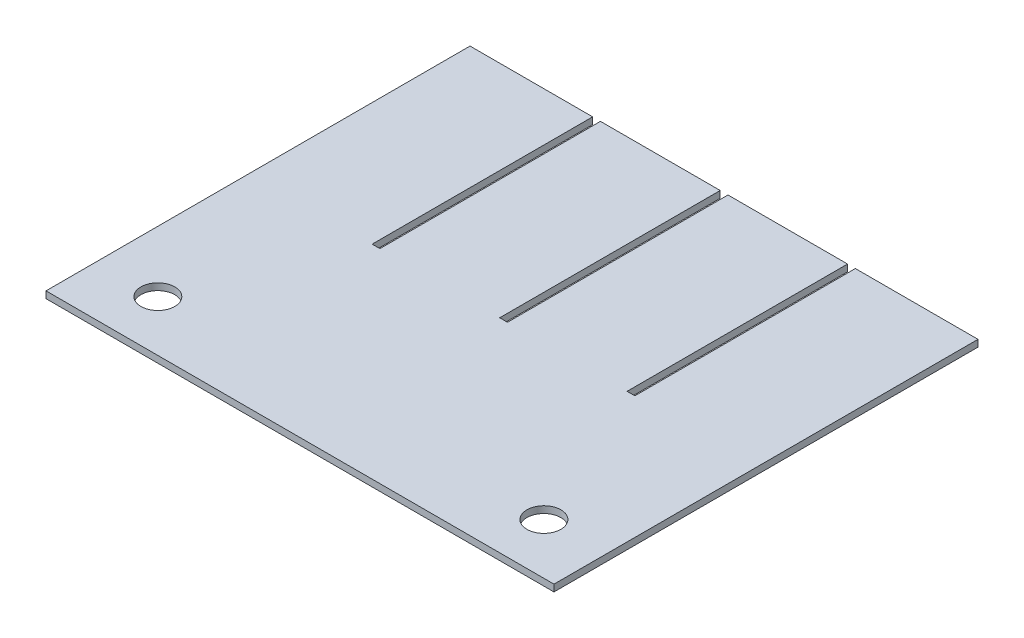
SolidWorks part; units mm, degrees
ref_plane "Front Plane" through (0, 0, 0) normal (0, 0, 1) x (1, 0, 0)
ref_plane "Top Plane" through (0, 0, 0) normal (0, 1, 0) x (1, 0, 0)
ref_plane "Right Plane" through (0, 0, 0) normal (1, 0, 0) x (0, 0, -1)
sketch "Sketch1" plane through (0, 0, 0) normal (0, 1, 0) x (1, 0, 0)
  line L0 (1.175, 62.5) -> (36.425, 62.5)
  line L1 (-74.875, 62.5) -> (-38.725, 62.5)
  line L2 (-74.875, 62.5) -> (-74.875, -62.5)
  line L3 (-74.875, -62.5) -> (74.875, -62.5)
  line L4 (74.875, 62.5) -> (74.875, -62.5)
  line L5 (-74.875, 62.5) -> (74.875, -62.5) construction
  line L6 (-74.875, -62.5) -> (74.875, 62.5) construction
  line L8 (-1.125, 62.5) -> (-1.125, -2.5)
  line L9 (-1.125, -2.5) -> (1.175, -2.5)
  line L10 (1.175, 62.5) -> (1.175, -2.5)
  line L11 (0, -7.6087) -> (0, 12.3363) construction
  line L13 (-38.725, 62.5) -> (-38.725, -2.5)
  line L14 (-38.725, -2.5) -> (-36.425, -2.5)
  line L15 (-36.425, 62.5) -> (-36.425, -2.5)
  line L16 (38.725, -2.5) -> (36.425, -2.5)
  line L17 (36.425, 62.5) -> (36.425, -2.5)
  line L19 (38.725, 62.5) -> (38.725, -2.5)
  line L20 (-36.425, 62.5) -> (-1.125, 62.5)
  line L21 (38.725, 62.5) -> (74.875, 62.5)
  line L22 (0.025, -2.5) -> (0.025, 10.5244) construction
  circle A0 centre (-56.905, -47.5) radius 5
  circle A1 centre (56.905, -47.5) radius 5
  point P0 (0, 0)
  dimension "D9" = 10
  dimension "D10" = 10
  dimension "D1" = 149.75
  dimension "D2" = 125
  dimension "D3" = 2.3
  dimension "D4" = 65
  dimension "D5" = 35.3
  dimension "D6" = 65
  dimension "D7" = 2.3
  dimension "D8" = 36.15
  dimension "D11" = 15
  dimension "D12" = 15
extrude "Boss-Extrude1" add sketch "Sketch1" along normal blind 2
